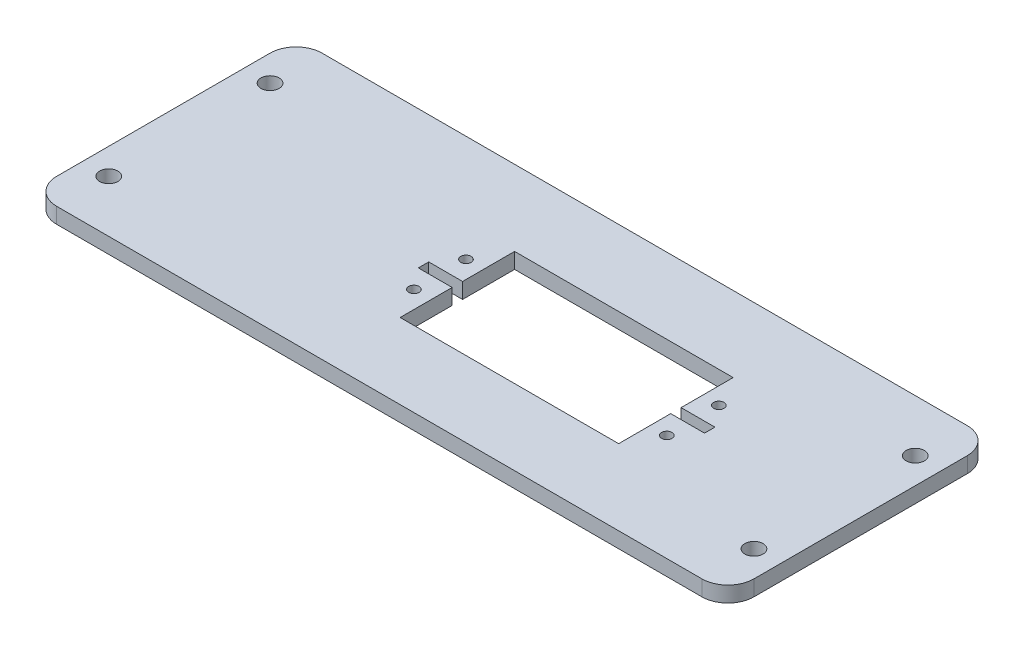
SolidWorks part; units mm, degrees
ref_plane "정면" through (0, 0, 0) normal (0, 0, 1) x (1, 0, 0)
ref_plane "윗면" through (0, 0, 0) normal (0, 1, 0) x (1, 0, 0)
ref_plane "우측면" through (0, 0, 0) normal (1, 0, 0) x (0, 0, -1)
sketch "스케치1" plane through (0, 0, 0) normal (0, 1, 0) x (1, 0, 0)
  line L1 (-67, 25.5) -> (67, 25.5)
  line L2 (-67, 25.5) -> (-67, -25.5)
  line L3 (-67, -25.5) -> (67, -25.5)
  line L4 (67, 25.5) -> (67, -25.5)
  line L5 (-67, 25.5) -> (67, -25.5) construction
  line L6 (-67, -25.5) -> (67, 25.5) construction
  point P0 (0, 0)
  dimension "D1" = 51
  dimension "D2" = 134
extrude "보스-돌출1" add sketch "스케치1" along normal blind 3
sketch "스케치2" plane through (0, 3, 0) normal (0, 1, 0) x (1, 0, 0)
  line L0 (-67, 25.5) -> (-67, -25.5) construction
  line L1 (-62, 15.5) -> (62, 15.5) construction
  line L2 (-62, 15.5) -> (-62, -15.5) construction
  line L3 (-62, -15.5) -> (62, -15.5) construction
  line L4 (62, 15.5) -> (62, -15.5) construction
  line L5 (-62, 15.5) -> (62, -15.5) construction
  line L6 (-62, -15.5) -> (62, 15.5) construction
  line L8 (67, 25.5) -> (-67, 25.5) construction
  circle A0 centre (-62, 15.5) radius 1.75
  circle A1 centre (-62, -15.5) radius 1.75
  circle A2 centre (62, 15.5) radius 1.75
  circle A3 centre (62, -15.5) radius 1.75
  point P0 (0, 0)
  dimension "D3" = 3.5
  dimension "D1" = 5
  dimension "D2" = 10
extrude "컷-돌출1" cut sketch "스케치2" against normal up to next
sketch "스케치3" plane through (0, 3, 0) normal (0, 1, 0) x (1, 0, 0)
  line L0 (-67, 0) -> (67, 0) construction
  line L1 (-10.5, 11) -> (31.5, 11)
  line L2 (-10.5, 11) -> (-10.5, 1)
  line L3 (-10.5, -11) -> (31.5, -11)
  line L4 (31.5, 11) -> (31.5, 1)
  line L5 (-10.5, 11) -> (31.5, -11) construction
  line L6 (-10.5, -11) -> (31.5, 11) construction
  line L7 (-67, 25.5) -> (-67, -25.5) construction
  line L8 (67, -25.5) -> (67, 25.5) construction
  line L10 (-13.85, 5) -> (34.75, 5) construction
  line L11 (-13.85, 5) -> (-13.85, -5) construction
  line L12 (-13.85, -5) -> (34.75, -5) construction
  line L13 (34.75, 5) -> (34.75, -5) construction
  line L14 (-13.85, 5) -> (34.75, -5) construction
  line L15 (-13.85, -5) -> (34.75, 5) construction
  line L16 (-10.5, -1) -> (-10.5, -11)
  line L17 (-17, 1) -> (-10.5, 1)
  line L18 (-17, 1) -> (-17, -1)
  line L19 (-17, -1) -> (-10.5, -1)
  line L21 (31.5, -1) -> (31.5, -11)
  line L23 (31.5, 1) -> (38, 1)
  line L25 (31.5, -1) -> (38, -1)
  line L26 (38, 1) -> (38, -1)
  circle A0 centre (-13.85, 5) radius 1
  circle A1 centre (-13.85, -5) radius 1
  circle A2 centre (34.75, 5) radius 1
  circle A3 centre (34.75, -5) radius 1
  point P0 (10.5, 0)
  point P12 (10.45, 0)
  point P21 (-10.5, 0)
  point P26 (31.5, 0)
  dimension "D6" = 2
  dimension "D1" = 42
  dimension "D2" = 22
  dimension "D3" = 31.5
  dimension "D4" = 3.35
  dimension "D5" = 3.25
  dimension "D7" = 6.5
  dimension "D8" = 10
  dimension "D9" = 6.5
  dimension "D10" = 2
  dimension "D11" = 2
extrude "컷-돌출2" cut sketch "스케치3" against normal up to next
fillet "필렛1" radius 5 4 edges at (-67, 1.5, 25.5) (-67, 1.5, -25.5) (67, 1.5, -25.5) (67, 1.5, 25.5)
